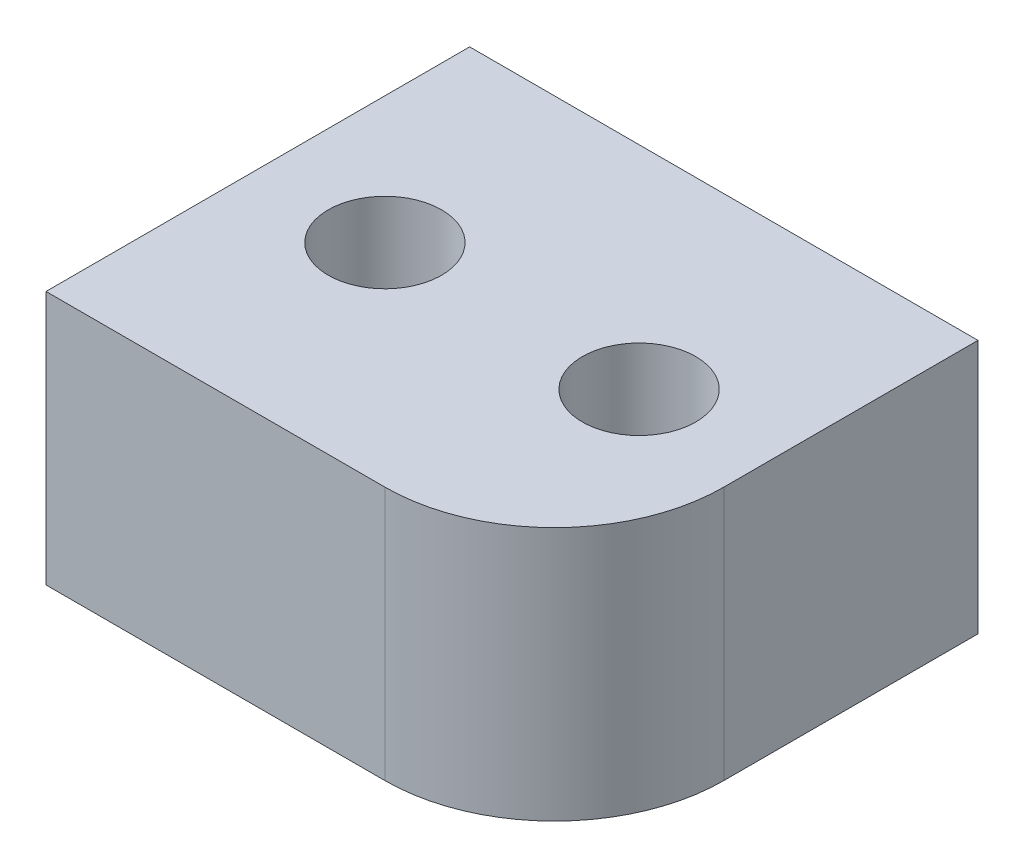
SolidWorks part; units mm, degrees
ref_plane "Front Plane" through (0, 0, 0) normal (0, 0, 1) x (1, 0, 0)
ref_plane "Top Plane" through (0, 0, 0) normal (0, 1, 0) x (1, 0, 0)
ref_plane "Right Plane" through (0, 0, 0) normal (1, 0, 0) x (0, 0, -1)
sketch "Sketch1" plane through (0, 0, 0) normal (0, 1, 0) x (1, 0, 0)
  line L0 (7.62, 12.7) -> (7.62, 0) construction
  line L1 (0, 0) -> (15.24, 0)
  line L2 (0, 0) -> (0, 12.7)
  line L3 (0, 12.7) -> (15.24, 12.7)
  line L4 (15.24, 0) -> (15.24, 12.7)
  line L5 (3.81, 6.35) -> (11.43, 6.35) construction
  circle A0 centre (11.43, 6.35) radius 1.7
  circle A1 centre (3.81, 6.35) radius 1.7
  point P12 (7.62, 6.35)
  point P13 (7.62, 6.35)
  dimension "D3" = 3.4
  dimension "D1" = 15.24
  dimension "D2" = 12.7
  dimension "D4" = 7.62
extrude "Boss-Extrude1" add sketch "Sketch1" along normal blind 7.62
fillet "Fillet1" radius 5.08 1 edges at (15.24, 3.81, 0)
